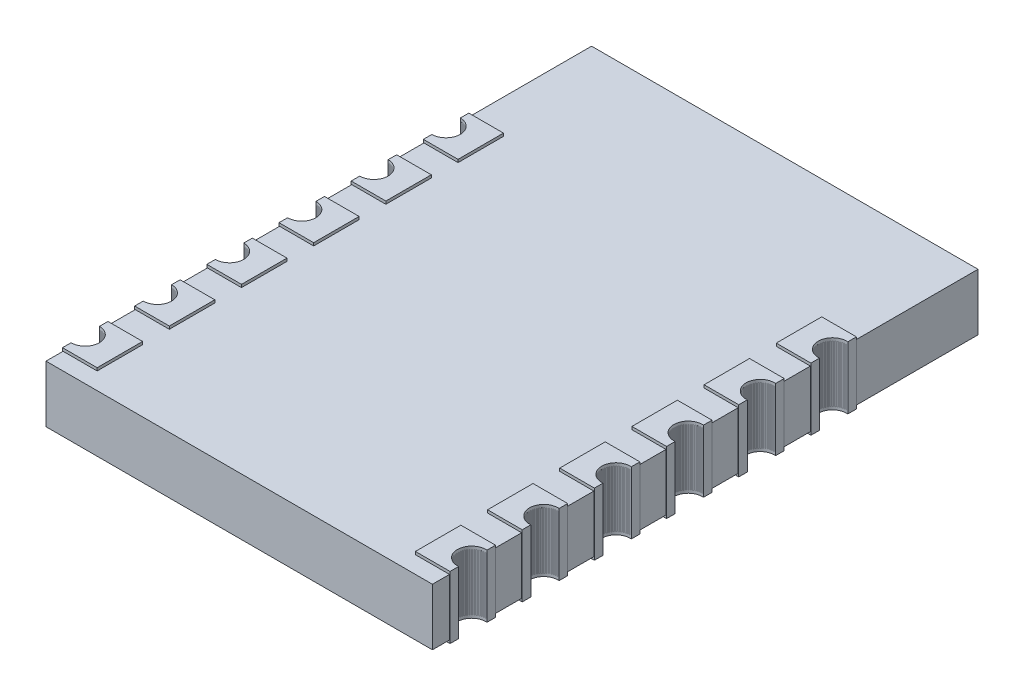
SolidWorks part; units mm, degrees
ref_plane "前视基准面" through (0, 0, 0) normal (0, 0, 1) x (1, 0, 0)
ref_plane "上视基准面" through (0, 0, 0) normal (0, 1, 0) x (1, 0, 0)
ref_plane "右视基准面" through (0, 0, 0) normal (1, 0, 0) x (0, 0, -1)
sketch "草图1" plane through (0, 0, 0) normal (0, 1, 0) x (1, 0, 0)
  line L1 (0, 0) -> (6.8, 0)
  line L2 (0, 0) -> (0, 9.6)
  line L3 (0, 9.6) -> (6.8, 9.6)
  line L4 (6.8, 0) -> (6.8, 9.6)
  dimension "D1" = 9.6
  dimension "D2" = 6.8
extrude "凸台-拉伸1" add sketch "草图1" along normal blind 1
sketch "草图2" plane through (0, 1, 0) normal (0, 1, 0) x (1, 0, 0)
  line L0 (0, 9.6) -> (0, 0) construction
  line L2 (-0.6, 1.1) -> (0.6, 1.1) construction
  line L3 (-0.6, 1.1) -> (-0.6, 0.3) construction
  line L4 (-0.6, 0.3) -> (0.6, 0.3) construction
  line L5 (0.6, 1.1) -> (0.6, 0.3)
  line L6 (-0.6, 1.1) -> (0.6, 0.3) construction
  line L7 (-0.6, 0.3) -> (0.6, 1.1) construction
  line L30 (3.4, 9.6) -> (3.4, 0) construction
  line L31 (6.8, 9.6) -> (0, 9.6) construction
  line L32 (0, 0) -> (6.8, 0) construction
  line L33 (0.6, 2.37) -> (0.6, 1.57)
  line L34 (-0.01, 2.37) -> (-0.01, 1.57)
  line L35 (-0.01, 1.57) -> (0.6, 1.57)
  line L36 (0.6, 2.37) -> (-0.01, 2.37)
  line L37 (-0.6, 2.37) -> (0.6, 2.37) construction
  line L62 (-0.01, 1.1) -> (-0.01, 0.3)
  line L63 (-0.01, 0.3) -> (0.6, 0.3)
  line L64 (0.6, 1.1) -> (-0.01, 1.1)
  line L65 (-0.6, 2.37) -> (-0.6, 1.57) construction
  line L66 (-0.6, 1.57) -> (0.6, 1.57) construction
  line L67 (-0.6, 2.37) -> (0.6, 1.57) construction
  line L68 (-0.6, 1.57) -> (0.6, 2.37) construction
  line L69 (0.6, 3.64) -> (0.6, 2.84)
  line L70 (-0.01, 3.64) -> (-0.01, 2.84)
  line L71 (-0.01, 2.84) -> (0.6, 2.84)
  line L72 (0.6, 3.64) -> (-0.01, 3.64)
  line L73 (-0.6, 3.64) -> (0.6, 3.64) construction
  line L74 (-0.6, 3.64) -> (-0.6, 2.84) construction
  line L75 (-0.6, 2.84) -> (0.6, 2.84) construction
  line L76 (-0.6, 3.64) -> (0.6, 2.84) construction
  line L77 (-0.6, 2.84) -> (0.6, 3.64) construction
  line L78 (0.6, 4.91) -> (0.6, 4.11)
  line L79 (-0.01, 4.91) -> (-0.01, 4.11)
  line L80 (-0.01, 4.11) -> (0.6, 4.11)
  line L81 (0.6, 4.91) -> (-0.01, 4.91)
  line L82 (-0.6, 4.91) -> (0.6, 4.91) construction
  line L83 (-0.6, 4.91) -> (-0.6, 4.11) construction
  line L84 (-0.6, 4.11) -> (0.6, 4.11) construction
  line L85 (-0.6, 4.91) -> (0.6, 4.11) construction
  line L86 (-0.6, 4.11) -> (0.6, 4.91) construction
  line L87 (0.6, 6.18) -> (0.6, 5.38)
  line L88 (-0.01, 6.18) -> (-0.01, 5.38)
  line L89 (-0.01, 5.38) -> (0.6, 5.38)
  line L90 (0.6, 6.18) -> (-0.01, 6.18)
  line L91 (-0.6, 6.18) -> (0.6, 6.18) construction
  line L92 (-0.6, 6.18) -> (-0.6, 5.38) construction
  line L93 (-0.6, 5.38) -> (0.6, 5.38) construction
  line L94 (-0.6, 6.18) -> (0.6, 5.38) construction
  line L95 (-0.6, 5.38) -> (0.6, 6.18) construction
  line L96 (0.6, 7.45) -> (0.6, 6.65)
  line L97 (-0.01, 7.45) -> (-0.01, 6.65)
  line L98 (-0.01, 6.65) -> (0.6, 6.65)
  line L99 (0.6, 7.45) -> (-0.01, 7.45)
  line L100 (-0.6, 7.45) -> (0.6, 7.45) construction
  line L101 (-0.6, 7.45) -> (-0.6, 6.65) construction
  line L102 (-0.6, 6.65) -> (0.6, 6.65) construction
  line L103 (-0.6, 7.45) -> (0.6, 6.65) construction
  line L104 (-0.6, 6.65) -> (0.6, 7.45) construction
  line L105 (7.4, 6.65) -> (6.2, 7.45) construction
  line L106 (7.4, 7.45) -> (6.2, 6.65) construction
  line L107 (7.4, 6.65) -> (6.2, 6.65) construction
  line L108 (7.4, 7.45) -> (7.4, 6.65) construction
  line L109 (7.4, 7.45) -> (6.2, 7.45) construction
  line L110 (7.4, 5.38) -> (6.2, 6.18) construction
  line L111 (7.4, 6.18) -> (6.2, 5.38) construction
  line L112 (7.4, 5.38) -> (6.2, 5.38) construction
  line L113 (7.4, 6.18) -> (7.4, 5.38) construction
  line L114 (7.4, 6.18) -> (6.2, 6.18) construction
  line L115 (7.4, 4.11) -> (6.2, 4.91) construction
  line L116 (7.4, 4.91) -> (6.2, 4.11) construction
  line L117 (7.4, 4.11) -> (6.2, 4.11) construction
  line L118 (7.4, 4.91) -> (7.4, 4.11) construction
  line L119 (7.4, 4.91) -> (6.2, 4.91) construction
  line L120 (7.4, 2.84) -> (6.2, 3.64) construction
  line L121 (7.4, 3.64) -> (6.2, 2.84) construction
  line L122 (7.4, 2.84) -> (6.2, 2.84) construction
  line L123 (7.4, 3.64) -> (7.4, 2.84) construction
  line L124 (7.4, 3.64) -> (6.2, 3.64) construction
  line L125 (7.4, 1.57) -> (6.2, 2.37) construction
  line L126 (7.4, 2.37) -> (6.2, 1.57) construction
  line L127 (7.4, 1.57) -> (6.2, 1.57) construction
  line L128 (7.4, 2.37) -> (7.4, 1.57) construction
  line L129 (7.4, 2.37) -> (6.2, 2.37) construction
  line L130 (7.4, 0.3) -> (6.2, 1.1) construction
  line L131 (7.4, 1.1) -> (6.2, 0.3) construction
  line L132 (7.4, 0.3) -> (6.2, 0.3) construction
  line L133 (7.4, 1.1) -> (7.4, 0.3) construction
  line L134 (7.4, 1.1) -> (6.2, 1.1) construction
  line L135 (6.2, 7.45) -> (6.81, 7.45)
  line L136 (6.81, 6.65) -> (6.2, 6.65)
  line L137 (6.81, 7.45) -> (6.81, 6.65)
  line L138 (6.2, 7.45) -> (6.2, 6.65)
  line L139 (6.2, 6.18) -> (6.81, 6.18)
  line L140 (6.81, 5.38) -> (6.2, 5.38)
  line L141 (6.81, 6.18) -> (6.81, 5.38)
  line L142 (6.2, 6.18) -> (6.2, 5.38)
  line L143 (6.2, 4.91) -> (6.81, 4.91)
  line L144 (6.81, 4.11) -> (6.2, 4.11)
  line L145 (6.81, 4.91) -> (6.81, 4.11)
  line L146 (6.2, 4.91) -> (6.2, 4.11)
  line L147 (6.2, 3.64) -> (6.81, 3.64)
  line L148 (6.81, 2.84) -> (6.2, 2.84)
  line L149 (6.81, 3.64) -> (6.81, 2.84)
  line L150 (6.2, 3.64) -> (6.2, 2.84)
  line L151 (6.2, 1.1) -> (6.81, 1.1)
  line L152 (6.81, 0.3) -> (6.2, 0.3)
  line L153 (6.81, 1.1) -> (6.81, 0.3)
  line L154 (6.2, 2.37) -> (6.81, 2.37)
  line L155 (6.81, 1.57) -> (6.2, 1.57)
  line L156 (6.81, 2.37) -> (6.81, 1.57)
  line L157 (6.2, 2.37) -> (6.2, 1.57)
  line L158 (6.2, 1.1) -> (6.2, 0.3)
  point P0 (0, 0.7)
  point P1 (0, 0.7)
  point P8 (-0.01, 1.1)
  point P9 (-0.01, 0.3)
  point P15 (0, 1.97)
  point P16 (0, 1.97)
  point P21 (-0.01, 2.37)
  point P22 (-0.01, 1.57)
  point P25 (0, 3.24)
  point P26 (0, 3.24)
  point P31 (-0.01, 3.64)
  point P32 (-0.01, 2.84)
  point P39 (0, 4.51)
  point P40 (0, 4.51)
  point P45 (-0.01, 4.91)
  point P46 (-0.01, 4.11)
  point P49 (0, 5.78)
  point P50 (0, 5.78)
  point P55 (-0.01, 6.18)
  point P56 (-0.01, 5.38)
  point P59 (0, 7.05)
  point P60 (0, 7.05)
  point P67 (-0.01, 7.45)
  point P68 (-0.01, 6.65)
  point P105 (6.8, 7.05)
  point P106 (6.8, 5.78)
  point P107 (6.8, 4.51)
  point P108 (6.8, 3.24)
  point P109 (6.8, 1.97)
  point P110 (6.8, 0.7)
  dimension "D1" = 0.7
  dimension "D2" = 0.8
  dimension "D3" = 1.2
  dimension "D5" = 0.01
  dimension "D4" = 6
extrude "凸台-拉伸2" add sketch "草图2" against normal blind 1.05 and the other way blind 0.05 separate body
sketch "草图4" plane through (0, 1.05, 0) normal (0, 1, 0) x (1, 0, 0)
  line L0 (-0.01, 1.1) -> (-0.01, 0.3) construction
  circle A0 centre (-0.01, 0.7) radius 0.25
  circle A1 centre (6.79, 0.7) radius 0.25
  circle A2 centre (6.79, 1.97) radius 0.25
  circle A3 centre (6.79, 3.24) radius 0.25
  circle A4 centre (6.79, 4.51) radius 0.25
  circle A5 centre (6.79, 5.78) radius 0.25
  circle A6 centre (6.79, 7.05) radius 0.25
  circle A7 centre (-0.01, 1.97) radius 0.25
  circle A8 centre (-0.01, 3.24) radius 0.25
  circle A9 centre (-0.01, 4.51) radius 0.25
  circle A10 centre (-0.01, 5.78) radius 0.25
  circle A11 centre (-0.01, 7.05) radius 0.25
  dimension "D1" = 0.5
  dimension "D2" = 2
  dimension "D3" = 6
extrude "切除-拉伸2" cut sketch "草图4" against normal through all
